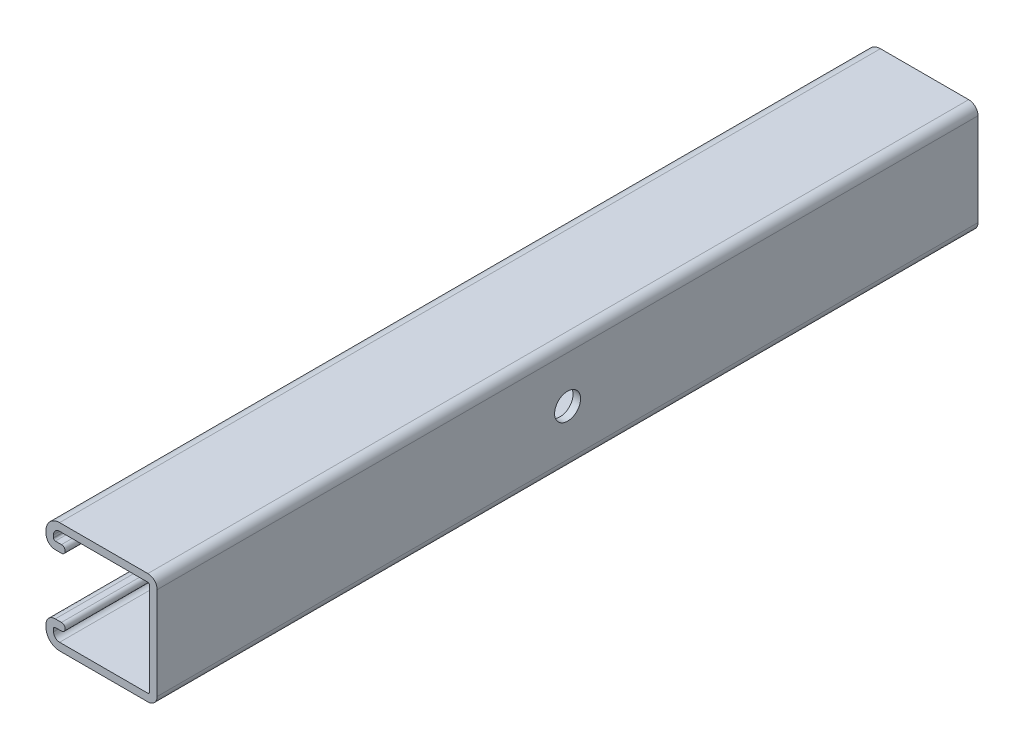
SolidWorks part; units mm, degrees
ref_plane "Front Plane" through (0, 0, 0) normal (0, 0, 1) x (1, 0, 0)
ref_plane "Top Plane" through (0, 0, 0) normal (0, 1, 0) x (1, 0, 0)
ref_plane "Right Plane" through (0, 0, 0) normal (1, 0, 0) x (0, 0, -1)
sketch "Sketch1" plane through (0, 0, 0) normal (0, 0, 1) x (1, 0, 0)
  line L0 (0, 0) -> (-41.275, 0) construction
  line L3 (-41.275, 20.6375) -> (0, 20.6375) construction
  line L4 (-41.275, 20.6375) -> (-41.275, -20.6375) construction
  line L5 (-41.275, -20.6375) -> (0, -20.6375) construction
  line L6 (0, 20.6375) -> (0, -20.6375) construction
  line L7 (-36.2267, 20.6375) -> (-3.4607, 20.6375)
  line L8 (0, 17.1767) -> (0, -17.1767)
  line L9 (-2.794, -17.1767) -> (-2.794, 17.1767)
  line L10 (-3.4608, 17.8435) -> (-36.2267, 17.8435)
  line L11 (-41.275, 15.5892) -> (-41.275, 14.5732)
  line L12 (-37.8142, 11.1125) -> (-35.5346, 11.1125)
  line L14 (-35.5346, 13.9065) -> (-37.8142, 13.9065)
  line L15 (-38.481, 14.5732) -> (-38.481, 15.5892)
  line L16 (-38.481, -14.5733) -> (-38.481, -15.5893)
  line L17 (-35.5346, -13.9065) -> (-37.8142, -13.9065)
  line L18 (-37.8142, -11.1125) -> (-35.5346, -11.1125)
  line L19 (-41.275, -15.5893) -> (-41.275, -14.5733)
  line L20 (-3.4607, -17.8435) -> (-36.2267, -17.8435)
  line L21 (-36.2267, -20.6375) -> (-3.4607, -20.6375)
  line L22 (-2.794, -20.6375) -> (-2.794, 20.6375) construction
  arc A1 (0, 17.1767) -> (-3.4607, 20.6375) centre (-3.4607, 17.1767) ccw
  arc A2 (-2.794, 17.1767) -> (-3.4608, 17.8435) centre (-3.4607, 17.1767) ccw
  arc A4 (-36.2267, 20.6375) -> (-41.275, 15.5892) centre (-36.2267, 15.5892) ccw
  arc A5 (-41.275, 14.5732) -> (-37.8142, 11.1125) centre (-37.8142, 14.5732) ccw
  arc A6 (-35.5346, 11.1125) -> (-35.5346, 13.9065) centre (-35.5346, 12.5095) ccw
  arc A7 (-37.8142, 13.9065) -> (-38.481, 14.5732) centre (-37.8142, 14.5732) cw
  arc A8 (-38.481, 15.5892) -> (-36.2267, 17.8435) centre (-36.2267, 15.5892) cw
  arc A9 (-38.481, -15.5893) -> (-36.2267, -17.8435) centre (-36.2267, -15.5893) ccw
  arc A10 (-37.8142, -13.9065) -> (-38.481, -14.5733) centre (-37.8142, -14.5733) ccw
  arc A11 (-35.5346, -11.1125) -> (-35.5346, -13.9065) centre (-35.5346, -12.5095) cw
  arc A12 (-41.275, -14.5733) -> (-37.8142, -11.1125) centre (-37.8142, -14.5733) cw
  arc A13 (-36.2267, -20.6375) -> (-41.275, -15.5893) centre (-36.2267, -15.5893) cw
  arc A14 (-2.794, -17.1767) -> (-3.4607, -17.8435) centre (-3.4607, -17.1767) cw
  arc A15 (0, -17.1767) -> (-3.4607, -20.6375) centre (-3.4607, -17.1767) cw
  point P24 (0, 20.6375)
  point P65 (-2.794, 0)
  dimension "D1" = 3.4608
  dimension "D2" = 5.0482
  dimension "D3" = 3.4608
  dimension "Ht." = 41.275
  dimension "Wd." = 41.275
  dimension "Thk." = 2.794
  dimension "D4" = 9.525
  dimension "D5" = 7.1374
extrude "Boss-Extrude1" add sketch "Sketch1" against normal blind 304.8
sketch "Sketch3" plane through (0, 0, 0) normal (1, 0, 0) x (0, 0, -1)
  line L0 (0, 0) -> (304.8, 0) construction
  point P2 (101.6, 0)
  point P3 (203.2, 0)
  dimension "D1" = 101.6
  dimension "D2" = 101.6
  dimension "D3" = 304.8
sketch "Sketch4" plane through (0, 0, 0) normal (1, 0, 0) x (0, 0, -1)
  line L0 (0, 0) -> (304.8, 0) construction
  line L1 (304.8, -17.1767) -> (304.8, 17.1767) construction
  circle A0 centre (152.4, 0) radius 4.826
  point P7 (128.5542, 0)
  dimension "D1" = 9.652
extrude "Cut-Extrude1" cut sketch "Sketch4" against normal through all
equation "\"D3@Sketch3\" = \"Lg.@Boss-Extrude1\""
